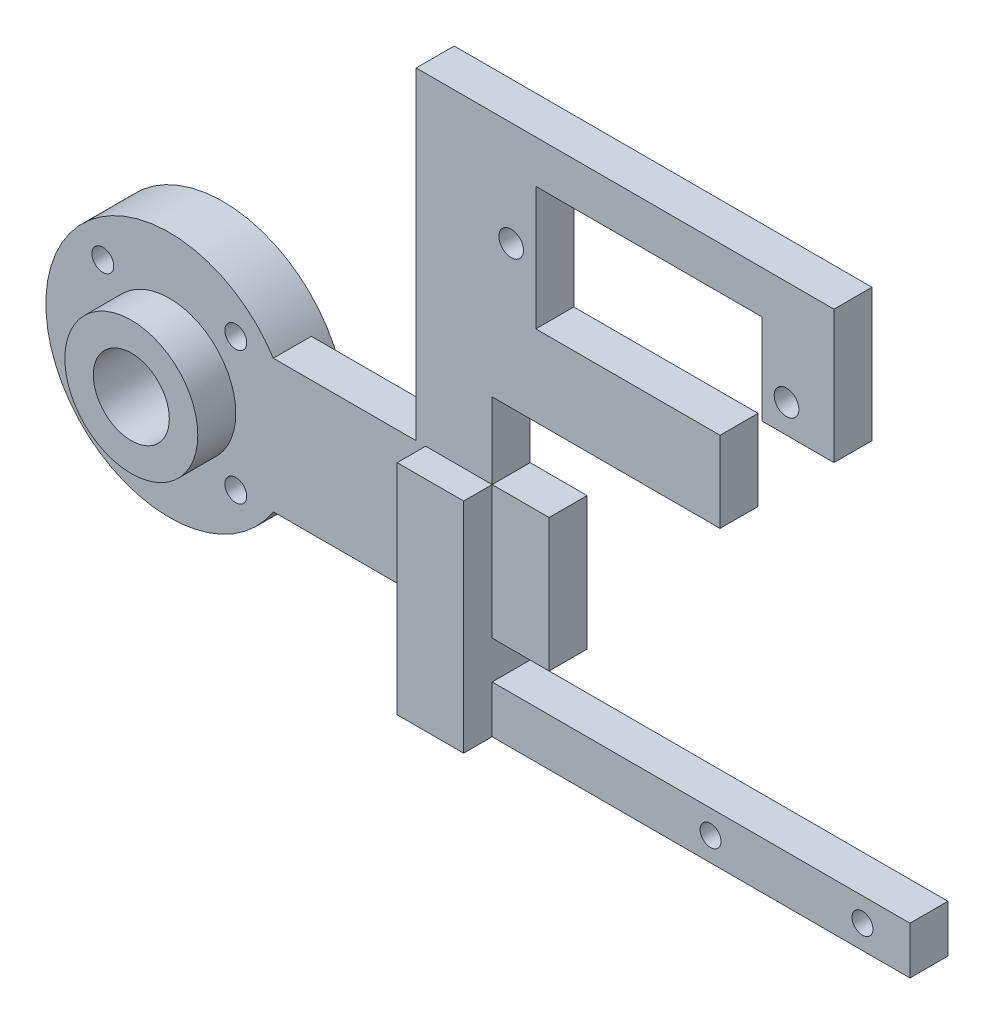
SolidWorks part; units mm, degrees
ref_plane "Front Plane" through (0, 0, 0) normal (0, 0, 1) x (1, 0, 0)
ref_plane "Top Plane" through (0, 0, 0) normal (0, 1, 0) x (1, 0, 0)
ref_plane "Right Plane" through (0, 0, 0) normal (1, 0, 0) x (0, 0, -1)
sketch "Elbow_horn_flange_profile" plane through (0, 0, 0) normal (0, 0, 1) x (1, 0, 0)
  circle A0 centre (0, 0) radius 13
  dimension "D1" = 26
extrude "Elbow_horn_flange" add sketch "Elbow_horn_flange_profile" along normal blind 4
sketch "Forearm_web_profile" plane through (0, 0, 0) normal (0, 0, 1) x (1, 0, 0)
  line L1 (0, -7) -> (40, -7)
  line L2 (0, -7) -> (0, 7)
  line L3 (0, 7) -> (40, 7)
  line L4 (40, -7) -> (40, 7)
  dimension "D1" = 40
  dimension "D2" = 14
extrude "Forearm_web" add sketch "Forearm_web_profile" along normal blind 4
sketch "Gripper_mount_rib_profile" plane through (0, 0, 0) normal (0, 0, 1) x (1, 0, 0)
  line L1 (26, 0) -> (34, 0)
  line L2 (26, 0) -> (26, 30)
  line L3 (26, 30) -> (34, 30)
  line L4 (34, 0) -> (34, 30)
  dimension "D1" = 8
  dimension "D2" = 30
extrude "Gripper_mount_rib" add sketch "Gripper_mount_rib_profile" along normal blind 4
sketch "Gripper_servo_mount_profile" plane through (0, 0, 0) normal (0, 0, 1) x (1, 0, 0)
  line L1 (26, 15) -> (70, 15)
  line L2 (26, 15) -> (26, 41)
  line L3 (26, 41) -> (70, 41)
  line L4 (70, 15) -> (70, 41)
  dimension "D1" = 44
  dimension "D2" = 26
extrude "Gripper_servo_mount" add sketch "Gripper_servo_mount_profile" along normal blind 4
sketch "Grip_SG90_body_clearance_profile" plane through (0, 0, 0) normal (0, 0, 1) x (1, 0, 0)
  line L1 (38.6, 23.5) -> (62.4, 23.5)
  line L2 (38.6, 23.5) -> (38.6, 36.5)
  line L3 (38.6, 36.5) -> (62.4, 36.5)
  line L4 (62.4, 23.5) -> (62.4, 36.5)
  dimension "D1" = 23.8
  dimension "D2" = 13
extrude "Grip_SG90_body_clearance" cut sketch "Grip_SG90_body_clearance_profile" along normal through all from offset 5
sketch "Moving_finger_sweep_relief_profile" plane through (0, 0, 0) normal (0, 0, 1) x (1, 0, 0)
  line L1 (58, 14) -> (71, 14)
  line L2 (58, 14) -> (58, 27)
  line L3 (58, 27) -> (71, 27)
  line L4 (71, 14) -> (71, 27)
  dimension "D1" = 13
  dimension "D2" = 13
extrude "Moving_finger_sweep_relief" cut sketch "Moving_finger_sweep_relief_profile" along normal through all from offset 5
sketch "Grip_servo_tab_fasteners_profile" plane through (0, 0, 0) normal (0, 0, 1) x (1, 0, 0)
  circle A0 centre (36, 30) radius 1.3
  circle A1 centre (65, 30) radius 1.3
  dimension "D1" = 2.6
  dimension "D2" = 2.6
extrude "Grip_servo_tab_fasteners" cut sketch "Grip_servo_tab_fasteners_profile" along normal through all from offset 50
sketch "Fixed_finger_spine_profile" plane through (0, 0, 0) normal (0, 0, 1) x (1, 0, 0)
  line L1 (30, -16) -> (78, -16)
  line L2 (30, -16) -> (30, -11)
  line L3 (30, -11) -> (78, -11)
  line L4 (78, -16) -> (78, -11)
  dimension "D1" = 48
  dimension "D2" = 5
extrude "Fixed_finger_spine" add sketch "Fixed_finger_spine_profile" along normal blind 4
sketch "Fixed_finger_root_profile" plane through (0, 0, 0) normal (0, 0, 1) x (1, 0, 0)
  line L1 (27, -16) -> (34, -16)
  line L2 (27, -16) -> (27, 7)
  line L3 (27, 7) -> (34, 7)
  line L4 (34, -16) -> (34, 7)
  dimension "D1" = 7
  dimension "D2" = 23
extrude "Fixed_finger_root" add sketch "Fixed_finger_root_profile" along normal blind 7
sketch "Elbow_center_screw_access_profile" plane through (0, 0, 0) normal (0, 0, 1) x (1, 0, 0)
  circle A0 centre (0, 0) radius 4
  dimension "D1" = 8
extrude "Elbow_center_screw_access" cut sketch "Elbow_center_screw_access_profile" along normal through all from offset 50
sketch "Elbow_dowel_support_hub_profile" plane through (0, 0, 0) normal (0, 0, 1) x (1, 0, 0)
  circle A0 centre (0, 0) radius 7
  circle A1 centre (0, 0) radius 4
  dimension "D1" = 14
  dimension "D2" = 8
extrude "Elbow_dowel_support_hub" add sketch "Elbow_dowel_support_hub_profile" along normal blind 4 from offset 4
sketch "Captured_horn_key_boss_profile" plane through (0, 0, 0) normal (0, 0, 1) x (1, 0, 0)
  circle A0 centre (0, 0) radius 13
  dimension "D1" = 26
extrude "Captured_horn_key_boss" add sketch "Captured_horn_key_boss_profile" along normal blind 1.65 from offset 1.65
sketch "Stock_horn_pocket_Hub" plane through (0, 0, 0) normal (0, 0, 1) x (1, 0, 0)
  circle A0 centre (0, 0) radius 3.55
  dimension "D1" = 7.1
extrude "Key_pocket_Hub" cut sketch "Stock_horn_pocket_Hub" along normal blind 1.65 from offset 1.65
sketch "Stock_horn_pocket_Horizontal" plane through (0, 0, 0) normal (0, 0, 1) x (1, 0, 0)
  line L1 (-8.15, -2.1) -> (8.15, -2.1)
  line L2 (-8.15, -2.1) -> (-8.15, 2.1)
  line L3 (-8.15, 2.1) -> (8.15, 2.1)
  line L4 (8.15, -2.1) -> (8.15, 2.1)
  dimension "D1" = 16.3
  dimension "D2" = 4.2
extrude "Key_pocket_Horizontal" cut sketch "Stock_horn_pocket_Horizontal" along normal blind 1.65 from offset 1.65
sketch "Stock_horn_pocket_Vertical" plane through (0, 0, 0) normal (0, 0, 1) x (1, 0, 0)
  line L1 (-2.1, -8.15) -> (2.1, -8.15)
  line L2 (-2.1, -8.15) -> (-2.1, 8.15)
  line L3 (-2.1, 8.15) -> (2.1, 8.15)
  line L4 (2.1, -8.15) -> (2.1, 8.15)
  dimension "D1" = 4.2
  dimension "D2" = 16.3
extrude "Key_pocket_Vertical" cut sketch "Stock_horn_pocket_Vertical" along normal blind 1.65 from offset 1.65
sketch "Stock_horn_pocket_Rounded_tips" plane through (0, 0, 0) normal (0, 0, 1) x (1, 0, 0)
  circle A0 centre (8.15, 0) radius 2.1
  circle A1 centre (-8.15, 0) radius 2.1
  circle A2 centre (0, 8.15) radius 2.1
  circle A3 centre (0, -8.15) radius 2.1
  dimension "D1" = 4.2
  dimension "D2" = 4.2
  dimension "D3" = 4.2
  dimension "D4" = 4.2
extrude "Key_pocket_Rounded_tips" cut sketch "Stock_horn_pocket_Rounded_tips" along normal blind 1.65 from offset 1.65
sketch "Unmodified_horn_capture_M2_profile" plane through (0, 0, 0) normal (0, 0, 1) x (1, 0, 0)
  circle A0 centre (7, 7) radius 1.15
  circle A1 centre (-7, 7) radius 1.15
  circle A2 centre (-7, -7) radius 1.15
  circle A3 centre (7, -7) radius 1.15
  dimension "D1" = 2.3
  dimension "D2" = 2.3
  dimension "D3" = 2.3
  dimension "D4" = 2.3
extrude "Unmodified_horn_capture_M2" cut sketch "Unmodified_horn_capture_M2_profile" along normal through all from offset 50
sketch "Horn_center_hub_clearance" plane through (0, 0, 0) normal (0, 0, 1) x (1, 0, 0)
  circle A0 centre (0, 0) radius 4
  dimension "D1" = 8
extrude "Hub_clearance_in_key_boss_only" cut sketch "Horn_center_hub_clearance" along normal blind 1.65 from offset 1.65
sketch "Fixed_pad_keeper_fasteners_profile" plane through (0, 0, 0) normal (0, 0, 1) x (1, 0, 0)
  circle A0 centre (57, -13.5) radius 1.1
  circle A1 centre (73, -13.5) radius 1.1
  dimension "D1" = 2.2
  dimension "D2" = 2.2
extrude "Fixed_pad_keeper_fasteners" cut sketch "Fixed_pad_keeper_fasteners_profile" along normal through all from offset 50
